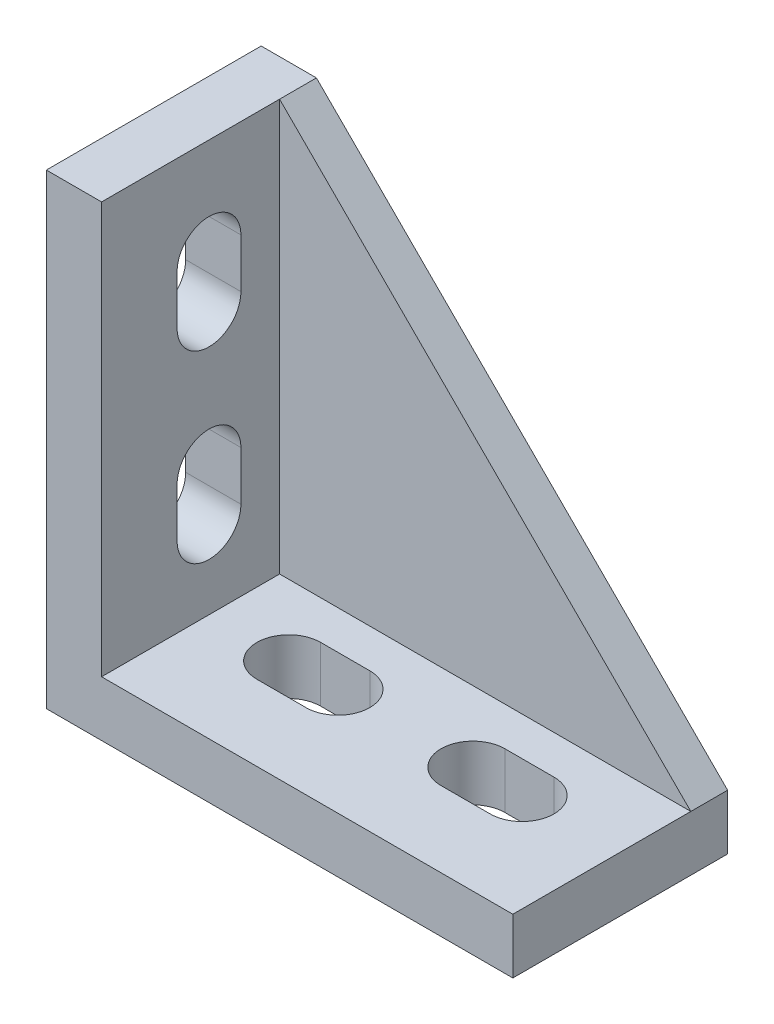
SolidWorks part; units mm, degrees
ref_plane "Front Plane" through (0, 0, 0) normal (0, 0, 1) x (1, 0, 0)
ref_plane "Top Plane" through (0, 0, 0) normal (0, 1, 0) x (1, 0, 0)
ref_plane "Right Plane" through (0, 0, 0) normal (1, 0, 0) x (0, 0, -1)
sketch "Sketch1" plane through (0, 0, 0) normal (0, 0, 1) x (1, 0, 0)
  line L0 (0, 0) -> (0, 38)
  line L1 (0, 38) -> (4.5, 38)
  line L2 (4.5, 38) -> (4.5, 4.5)
  line L3 (4.5, 4.5) -> (38, 4.5)
  line L4 (38, 4.5) -> (38, 0)
  line L5 (38, 0) -> (0, 0)
  dimension "D1" = 38
  dimension "D2" = 4.5
extrude "Boss-Extrude1" add sketch "Sketch1" along normal mid plane 17.5 contours L2 L3 L4 L5 L0 L1
sketch "Sketch2" plane through (0, 0, -8.75) normal (0, 0, -1) x (-1, 0, 0)
  line L0 (-4.5, 38) -> (-38, 4.5)
  line L1 (0, 38) -> (-4.5, 38) construction
  line L2 (0, 0) -> (0, 38) construction
  line L3 (-38, 0) -> (0, 0) construction
  line L4 (-38, 4.5) -> (-38, 0) construction
  line L5 (0, 38) -> (-4.5, 38)
  line L6 (0, 0) -> (0, 38)
  line L7 (-38, 0) -> (0, 0)
  line L8 (-38, 4.5) -> (-38, 0)
extrude "Boss-Extrude2" add sketch "Sketch2" against normal blind 3
sketch "Sketch3" plane through (0, 4.5, 0) normal (0, 1, 0) x (1, 0, 0)
  line L0 (30, 0) -> (26, 0) construction
  line L1 (30, -2.6) -> (26, -2.6)
  line L2 (30, 2.6) -> (26, 2.6)
  line L3 (11, 0) -> (15, 0) construction
  line L4 (11, 2.6) -> (15, 2.6)
  line L5 (11, -2.6) -> (15, -2.6)
  line L6 (38, -8.75) -> (38, 5.75) construction
  arc A0 (30, -2.6) -> (30, 2.6) centre (30, 0) ccw
  arc A1 (26, 2.6) -> (26, -2.6) centre (26, 0) ccw
  arc A2 (11, 2.6) -> (11, -2.6) centre (11, 0) ccw
  arc A3 (15, -2.6) -> (15, 2.6) centre (15, 0) ccw
  point P2 (28, 0)
  point P9 (13, 0)
  dimension "D1" = 2.6
  dimension "D2" = 4
  dimension "D3" = 10
  dimension "D4" = 15
extrude "Cut-Extrude1" cut sketch "Sketch3" against normal blind 4.5
sketch "Sketch4" plane through (4.5, 0, 0) normal (1, 0, 0) x (0, 0, -1)
  line L0 (0, 30) -> (0, 26) construction
  line L1 (2.6, 30) -> (2.6, 26)
  line L2 (-2.6, 30) -> (-2.6, 26)
  line L3 (0, 15) -> (0, 11) construction
  line L4 (2.6, 15) -> (2.6, 11)
  line L5 (-2.6, 15) -> (-2.6, 11)
  line L6 (-8.75, 38) -> (5.75, 38) construction
  arc A0 (2.6, 30) -> (-2.6, 30) centre (0, 30) ccw
  arc A1 (-2.6, 26) -> (2.6, 26) centre (0, 26) ccw
  arc A2 (2.6, 15) -> (-2.6, 15) centre (0, 15) ccw
  arc A3 (-2.6, 11) -> (2.6, 11) centre (0, 11) ccw
  point P2 (0, 28)
  point P7 (0, 13)
  dimension "D4" = 2.6
  dimension "D1" = 4
  dimension "D2" = 10
  dimension "D3" = 15
extrude "Cut-Extrude2" cut sketch "Sketch4" against normal blind 4.5
